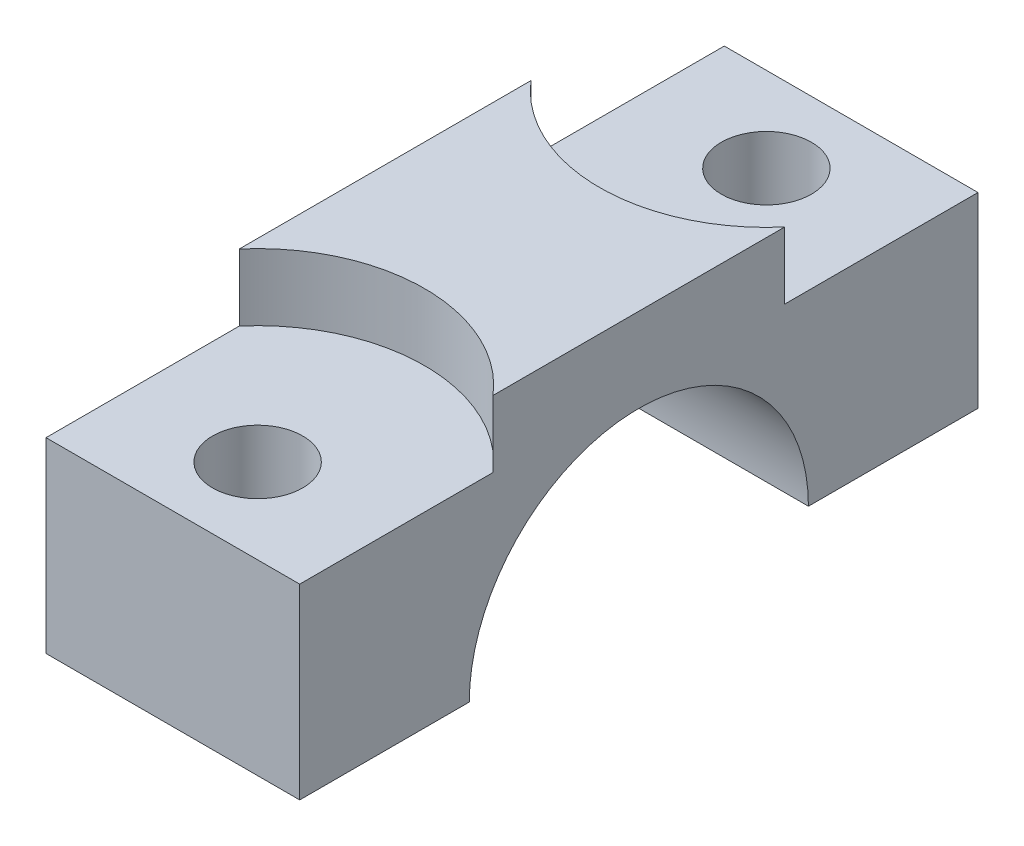
SolidWorks part; units mm, degrees
ref_plane "Front Plane" through (0, 0, 0) normal (0, 0, 1) x (1, 0, 0)
ref_plane "Top Plane" through (0, 0, 0) normal (0, 1, 0) x (1, 0, 0)
ref_plane "Right Plane" through (0, 0, 0) normal (1, 0, 0) x (0, 0, -1)
sketch "Sketch1" plane through (0, 0, 0) normal (1, 0, 0) x (0, 0, -1)
  line L0 (12.7, 0) -> (25.4, 0)
  line L1 (-25.4, 19) -> (25.4, 19)
  line L2 (-25.4, 19) -> (-25.4, 0)
  line L3 (-25.4, 0) -> (-12.7, 0)
  line L4 (25.4, 19) -> (25.4, 0)
  arc A0 (-12.7, 0) -> (12.7, 0) centre (0, 0) cw
  dimension "D1" = 50.8
  dimension "D3" = 12.7
  dimension "D2" = 19
extrude "Boss-Extrude1" add sketch "Sketch1" along normal mid plane 19
sketch "Sketch2" plane through (0, 0, 0) normal (0, -1, 0) x (1, 0, 0)
  line L0 (-9.5, 19.05) -> (9.5, 19.05) construction
  line L1 (-9.5, 25.4) -> (-9.5, 12.7) construction
  line L2 (9.5, 25.4) -> (9.5, 12.7) construction
  line L3 (-9.5, -19.05) -> (9.5, -19.05) construction
  line L4 (-9.5, -12.7) -> (-9.5, -25.4) construction
  line L5 (9.5, -12.7) -> (9.5, -25.4) construction
  point P12 (0, 19.05)
  point P13 (0, -19.05)
hole_wizard "CBORE for M12 Hex Head Cap Screw1" positions "Sketch3" profile "Sketch4" counterbore size "M12" standard "ISO"
sketch "Sketch3" plane through (0, 19, 0) normal (0, 1, 0) x (1, 0, 0)
  point P0 (0, 19.05)
  point P3 (0, -19.05)
sketch "Sketch4" plane through (0, 19, -19.05) normal (1, 0, 0) x (0, 0, 1)
  line L0 (0, 0) -> (0, 16.51)
  line L1 (0, 16.51) -> (3.375, 16.51)
  line L2 (3.375, 16.51) -> (3.375, 5)
  line L3 (3.375, 5) -> (12.5, 5)
  line L4 (12.5, 5) -> (12.5, 0)
  line L5 (12.5, 0) -> (0, 0)
  line L10 (0, 16.51) -> (-3.375, 16.51) construction
  line L11 (0, -6.35) -> (0, 107.95) construction
  dimension "Hole Dia." = 6.75
  dimension "Hole Depth" = 16.51
  dimension "C'Bore Dia." = 25
  dimension "C'Bore Depth" = 5
  dimension "Drill Angle" = 180
